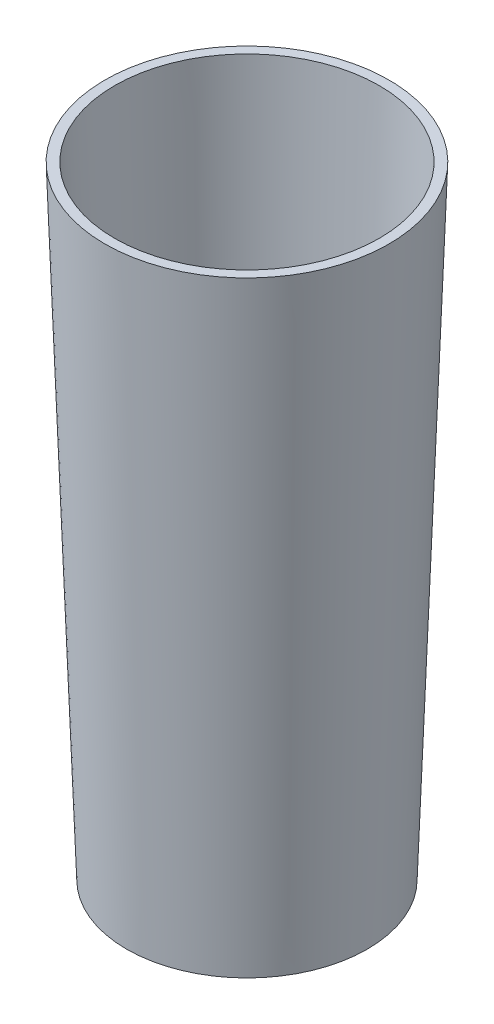
SolidWorks part; units mm, degrees
ref_plane "Front Plane" through (0, 0, 0) normal (0, 0, 1) x (1, 0, 0)
ref_plane "Top Plane" through (0, 0, 0) normal (0, 1, 0) x (1, 0, 0)
ref_plane "Right Plane" through (0, 0, 0) normal (1, 0, 0) x (0, 0, -1)
sketch "Sketch1" plane through (0, 0, 0) normal (0, 1, 0) x (1, 0, 0)
  circle A1 centre (0, 0) radius 6.195
  dimension "D2" = 12.39
extrude "Boss-Extrude1" add sketch "Sketch1" along normal blind 32 draft 2 contours A1 draft outward yes
sketch "Sketch3" plane through (0, 0, 0) normal (0, -1, 0) x (-1, 0, 0)
  circle A0 centre (0, 0) radius 5.695
  dimension "D1" = 11.39
extrude "Cut-Extrude1" cut sketch "Sketch3" against normal blind 50.7 draft 2 draft outward yes
